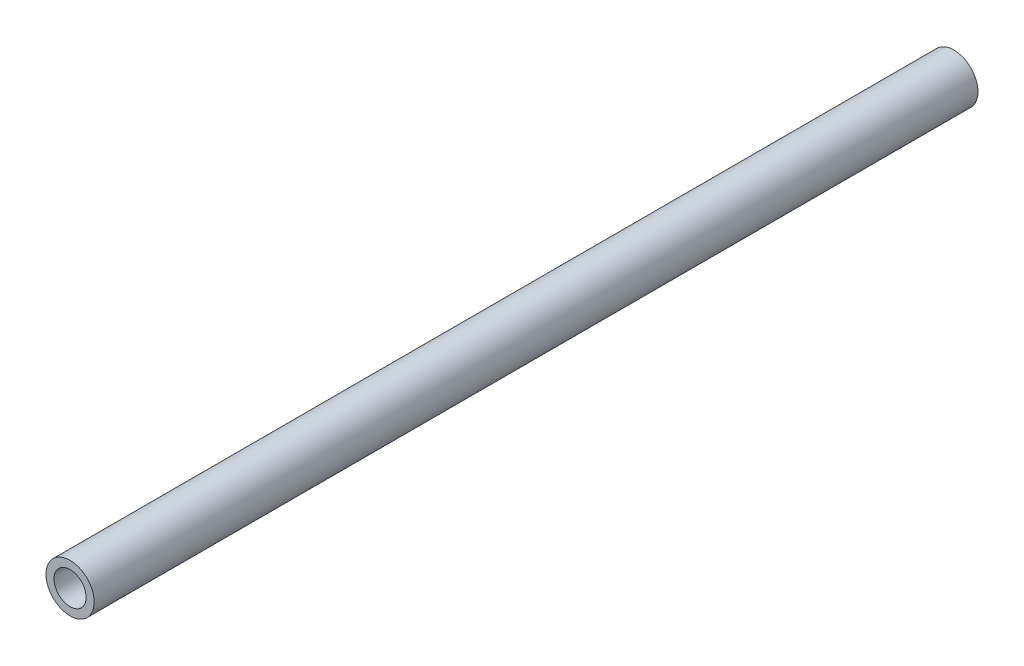
SolidWorks part; units mm, degrees
ref_plane "Front Plane" through (0, 0, 0) normal (0, 0, 1) x (1, 0, 0)
ref_plane "Top Plane" through (0, 0, 0) normal (0, 1, 0) x (1, 0, 0)
ref_plane "Right Plane" through (0, 0, 0) normal (1, 0, 0) x (0, 0, -1)
other "Configuration Table"
sketch "Sketch1" plane through (0, 0, 0) normal (0, 0, 1) x (1, 0, 0)
  circle A0 centre (0, 0) radius 6
  circle A1 centre (0, 0) radius 4
extrude "Boss-Extrude1" add sketch "Sketch1" along normal mid plane 220
